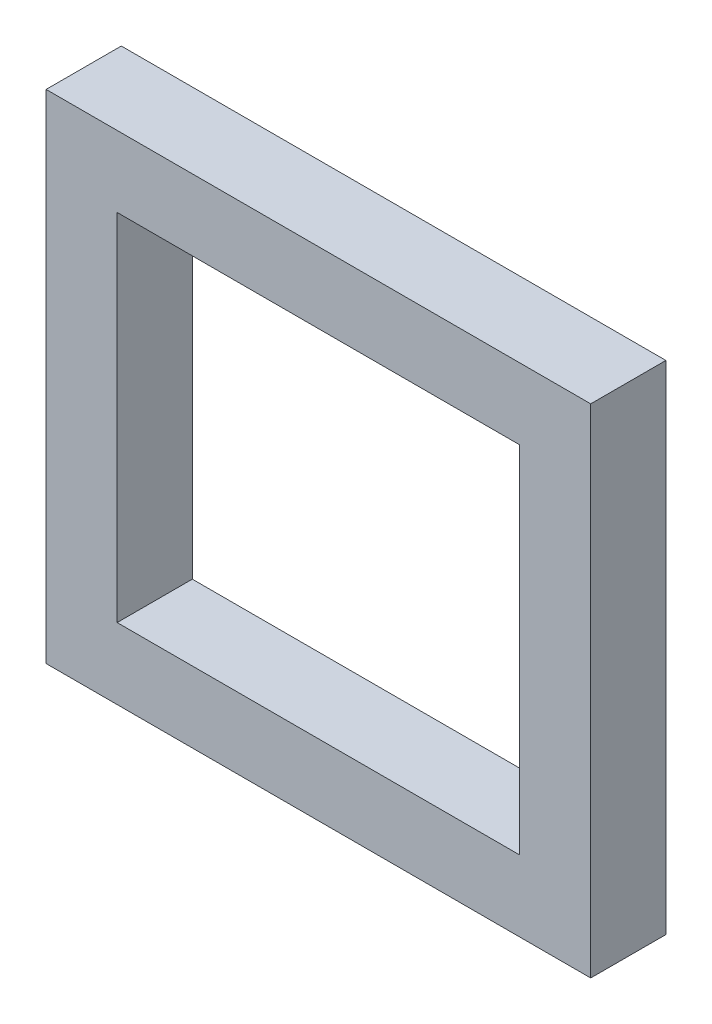
SolidWorks part; units mm, degrees
material "EPDM"
ref_plane "Front Plane" through (0, 0, 0) normal (0, 0, 1) x (1, 0, 0)
ref_plane "Top Plane" through (0, 0, 0) normal (0, 1, 0) x (1, 0, 0)
ref_plane "Right Plane" through (0, 0, 0) normal (1, 0, 0) x (0, 0, -1)
sketch "Sketch1" plane through (0, 0, 0) normal (0, 0, 1) x (1, 0, 0)
  line L1 (-11.5, -10.5) -> (11.5, -10.5)
  line L2 (-11.5, -10.5) -> (-11.5, 10.5)
  line L3 (-11.5, 10.5) -> (11.5, 10.5)
  line L4 (11.5, -10.5) -> (11.5, 10.5)
  line L5 (-11.5, -10.5) -> (11.5, 10.5) construction
  line L6 (-11.5, 10.5) -> (11.5, -10.5) construction
  line L7 (-8.5, -7.5) -> (8.5, -7.5)
  line L8 (-8.5, -7.5) -> (-8.5, 7.5)
  line L9 (-8.5, 7.5) -> (8.5, 7.5)
  line L10 (8.5, -7.5) -> (8.5, 7.5)
  line L11 (-8.5, -7.5) -> (8.5, 7.5) construction
  line L12 (-8.5, 7.5) -> (8.5, -7.5) construction
  point P0 (0, 0)
  point P6 (0, 0)
  dimension "D1" = 3
  dimension "D2" = 23
  dimension "D3" = 21
  dimension "D4" = 3
extrude "Boss-Extrude1" add sketch "Sketch1" along normal blind 3.175
